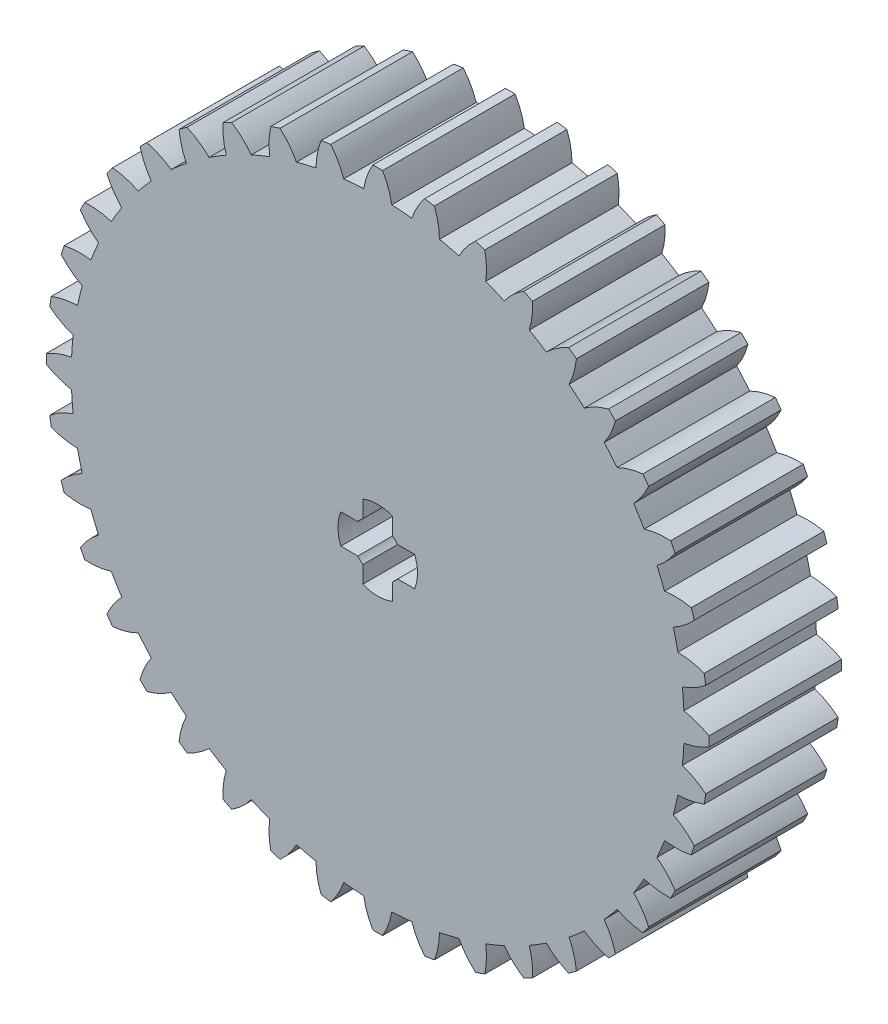
SolidWorks part; units mm, degrees
ref_plane "Front Plane" through (0, 0, 0) normal (0, 0, 1) x (1, 0, 0)
ref_plane "Top Plane" through (0, 0, 0) normal (0, 1, 0) x (1, 0, 0)
ref_plane "Right Plane" through (0, 0, 0) normal (1, 0, 0) x (0, 0, -1)
sketch "Sketch1" plane through (0, 0, 0) normal (0, 0, 1) x (1, 0, 0)
  circle A0 centre (0, 0) radius 18.5
  circle A1 centre (0, 0) radius 1.5
  dimension "D1" = 37
  dimension "D2" = 3
extrude "Boss-Extrude1" add sketch "Sketch1" along normal mid plane 8
sketch "Sketch3" plane through (0, 0, 4) normal (0, 0, 1) x (1, 0, 0)
  line L0 (0, 0) -> (0, 33.1941) construction
  line L1 (0, 0) -> (-2.5742, 32.7087) construction
  line L2 (0, 0) -> (2.6204, 33.2957) construction
  arc A2 (0.8485, 18.4805) -> (-0.8485, 18.4805) centre (0, 0) ccw
  arc A3 (0.2949, 19.9978) -> (-0.2949, 19.9978) centre (0, 0) ccw
  spline S0 degree 2 poles (-0.2949, 19.9978) (-0.708, 19.2899) (-0.8485, 18.4805) knots 0 0 0 1 1 1
  spline S1 degree 2 poles (0.2949, 19.9978) (0.708, 19.2899) (0.8485, 18.4805) knots 0 0 0 1 1 1
  dimension "D1" = 18.5
  dimension "D4" = 20
  dimension "D2" = 4.5
  dimension "D3" = 4.5
extrude "Boss-Extrude2" add sketch "Sketch3" against normal up to surface (8 mm away) up to face at (18.5, 0, -4)
pattern_circular "CirPattern2" count 40 over 360 about axis through (0, 0, 4) along (0, 0, -1) of "Boss-Extrude2"
sketch "Sketch4" plane through (0, 0, 4) normal (0, 0, 1) x (1, 0, 0)
  line L0 (-0.9, 2.2249) -> (-0.9, 0.9)
  line L1 (0.9, 2.2249) -> (0.9, 0.9)
  line L2 (-2.2249, 0.9) -> (-0.9, 0.9)
  line L3 (-2.2249, -0.9) -> (-0.9, -0.9)
  line L4 (0.9, 0.9) -> (2.2249, 0.9)
  line L5 (-0.9, -0.9) -> (-0.9, -2.2249)
  line L6 (0.9, -0.9) -> (2.2249, -0.9)
  line L7 (0.9, -0.9) -> (0.9, -2.2249)
  arc A0 (0.9, 2.2249) -> (-0.9, 2.2249) centre (0, 0) ccw
  arc A1 (-2.2249, 0.9) -> (-2.2249, -0.9) centre (0, 0) ccw
  arc A2 (-0.9, -2.2249) -> (0.9, -2.2249) centre (0, 0) ccw
  arc A3 (2.2249, -0.9) -> (2.2249, 0.9) centre (0, 0) ccw
  dimension "D1" = 4.8
  dimension "D2" = 0.9
  dimension "D3" = 0.9
  dimension "D4" = 0.9
  dimension "D5" = 0.9
extrude "Cut-Extrude1" cut sketch "Sketch4" against normal blind 10
